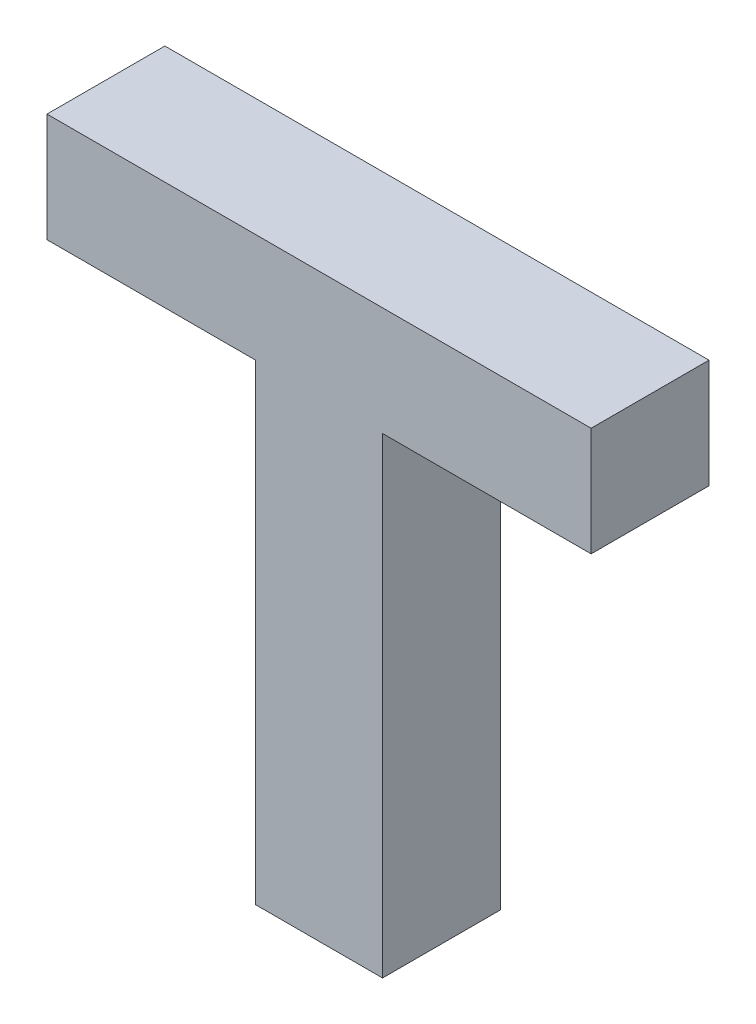
SolidWorks part; units mm, degrees
ref_plane "Front Plane" through (0, 0, 0) normal (0, 0, 1) x (1, 0, 0)
ref_plane "Top Plane" through (0, 0, 0) normal (0, 1, 0) x (1, 0, 0)
ref_plane "Right Plane" through (0, 0, 0) normal (1, 0, 0) x (0, 0, -1)
sketch "Sketch1" plane through (0, 0, 0) normal (0, 0, 1) x (1, 0, 0)
  line L1 (0, 0) -> (30, 0)
  line L2 (0, 0) -> (0, 32)
  line L3 (0, 32) -> (30, 32)
  line L4 (30, 0) -> (30, 32)
  dimension "D1" = 30
  dimension "D2" = 32
extrude "Boss-Extrude1" add sketch "Sketch1" along normal blind 6.5
sketch "Sketch2" plane through (0, 0, 6.5) normal (0, 0, 1) x (1, 0, 0)
  line L3 (0, 0) -> (11.5, 0)
  line L4 (0, 0) -> (0, 26)
  line L5 (0, 26) -> (11.5, 26)
  line L6 (11.5, 0) -> (11.5, 26)
  line L7 (30, 0) -> (18.5, 0)
  line L8 (30, 0) -> (30, 26)
  line L9 (30, 26) -> (18.5, 26)
  line L10 (18.5, 0) -> (18.5, 26)
  dimension "D1" = 7
  dimension "D2" = 26
extrude "Cut-Extrude1" cut sketch "Sketch2" against normal up to next
